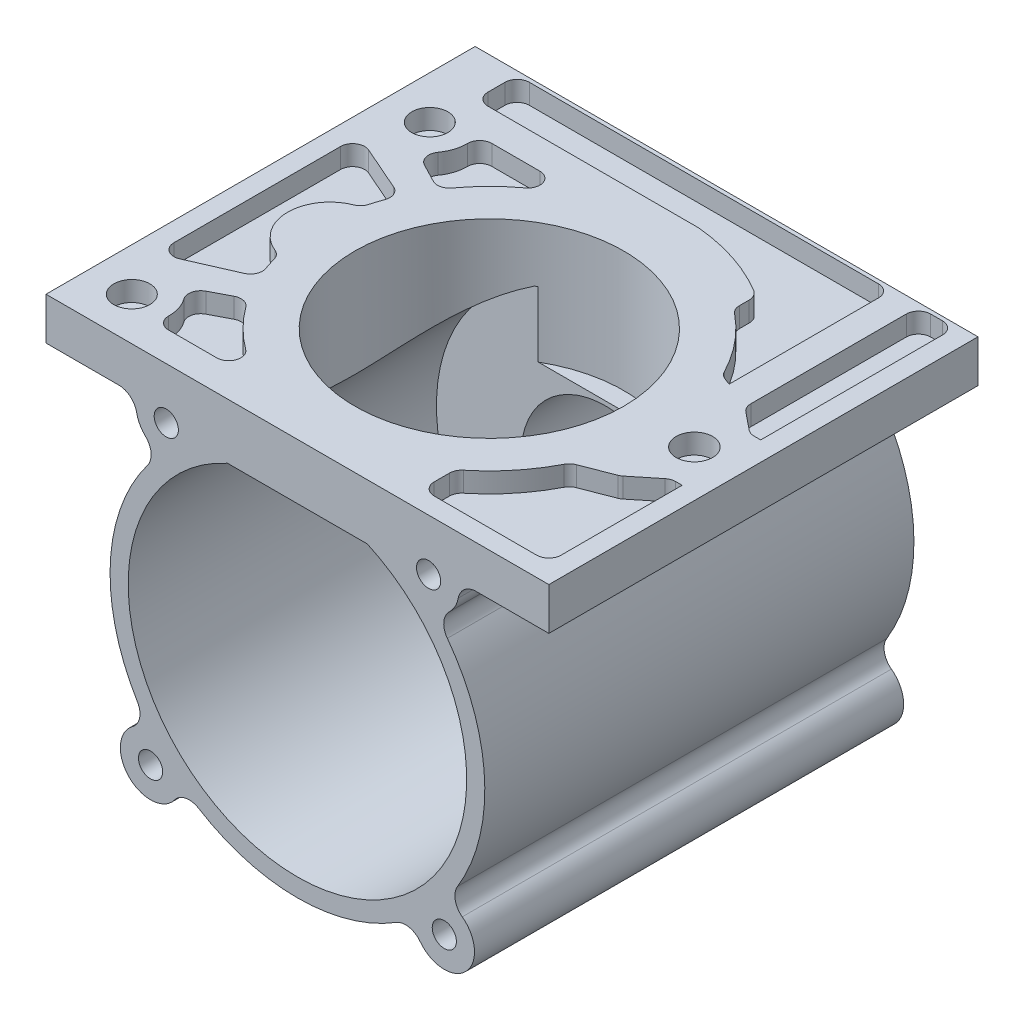
SolidWorks part; units mm, degrees
ref_plane "Front Plane" through (0, 0, 0) normal (0, 0, 1) x (1, 0, 0)
ref_plane "Top Plane" through (0, 0, 0) normal (0, 1, 0) x (1, 0, 0)
ref_plane "Right Plane" through (0, 0, 0) normal (1, 0, 0) x (0, 0, -1)
sketch "Sketch1" plane through (0, 0, 0) normal (0, 0, 1) x (1, 0, 0)
  line L0 (0, -28) -> (0, 25.5) construction
  line L1 (0, 25.5) -> (-11.565, 25.5)
  line L2 (0, 25.5) -> (11.565, 25.5)
  line L3 (0, 25.5) -> (0, 34.7) construction
  line L4 (-41.6, 34.7) -> (41.6, 34.7)
  line L5 (-41.6, 34.7) -> (-41.6, 27.7)
  line L6 (-41.6, 27.7) -> (-29.5581, 27.7)
  line L7 (41.6, 34.7) -> (41.6, 27.7)
  line L8 (41.6, 27.7) -> (29.5581, 27.7)
  line L9 (0, 0) -> (-24.3, -24.1) construction
  line L10 (0, -24.1) -> (-24.3, -24.1) construction
  line L11 (-21.7, 26.2) -> (0, 26.2) construction
  line L12 (-21.7, 26.2) -> (-24.3, -24.1) construction
  line L13 (-21.7, 28.2) -> (-21.7, 34.7) construction
  arc A0 (-11.565, 25.5) -> (11.565, 25.5) centre (0, 0) ccw
  arc A1 (-16.3237, -26.3541) -> (16.3237, -26.3541) centre (0, 0) ccw
  circle A2 centre (-24.3, -24.1) radius 2
  circle A3 centre (24.3, -24.1) radius 2
  circle A4 centre (-21.7, 26.2) radius 2
  circle A5 centre (21.7, 26.2) radius 2
  arc A6 (-26.6113, 25.2625) -> (-25.1401, 22.5715) centre (-21.7, 26.2) ccw
  arc A7 (-27.2697, -20.0774) -> (-20.3021, -27.1028) centre (-24.3, -24.1) ccw
  arc A8 (20.3021, -27.1028) -> (27.2697, -20.0774) centre (24.3, -24.1) ccw
  arc A9 (25.1401, 22.5715) -> (26.6113, 25.2625) centre (21.7, 26.2) ccw
  arc A10 (26.4881, -16.1053) -> (24.8038, 18.5949) centre (0, 0) ccw
  arc A11 (-24.8038, 18.5949) -> (-26.4881, -16.1053) centre (0, 0) ccw
  arc A12 (27.2697, -20.0774) -> (26.4881, -16.1053) centre (29.0515, -17.6639) cw
  arc A13 (20.3021, -27.1028) -> (16.3237, -26.3541) centre (17.9034, -28.9045) ccw
  arc A14 (-27.2697, -20.0774) -> (-26.4881, -16.1053) centre (-29.0515, -17.6639) ccw
  arc A15 (-20.3021, -27.1028) -> (-16.3237, -26.3541) centre (-17.9034, -28.9045) cw
  arc A16 (25.1401, 22.5715) -> (24.8038, 18.5949) centre (27.2042, 20.3945) ccw
  arc A17 (-26.6113, 25.2625) -> (-29.5581, 27.7) centre (-29.5581, 24.7) ccw
  arc A18 (-25.1401, 22.5715) -> (-24.8038, 18.5949) centre (-27.2042, 20.3945) cw
  arc A19 (26.6113, 25.2625) -> (29.5581, 27.7) centre (29.5581, 24.7) cw
  point P12 (0, 34.7)
  point P34 (24.416, -19.1013)
  point P43 (22.5494, 21.2727)
  point P48 (-22.5494, 21.2727)
  dimension "D1" = 56
  dimension "D2" = 3
  dimension "D4" = 24.3
  dimension "D5" = 21.7
  dimension "D6" = 4
  dimension "D12" = 3
  dimension "D13" = 3
  dimension "D14" = 3
  dimension "D3" = 83.2
  dimension "D7" = 50.3
  dimension "D8" = 6.5
  dimension "D9" = 7
  dimension "D10" = 9.2
  dimension "D11" = 53.5
extrude "Boss-Extrude1" add sketch "Sketch1" against normal blind 71
sketch "Sketch3" plane through (0, 0, -71) normal (0, 0, -1) x (-1, 0, 0)
  line L0 (-11.565, 25.5) -> (11.565, 25.5) construction
  line L1 (-11.565, 25.5) -> (11.565, 25.5)
  arc A0 (-11.565, 25.5) -> (11.565, 25.5) centre (0, 0) ccw construction
  arc A1 (-11.565, 25.5) -> (11.565, 25.5) centre (0, 0) ccw
extrude "Boss-Extrude2" add sketch "Sketch3" against normal blind 20
sketch "Sketch4" plane through (0, 34.7, 0) normal (0, 1, 0) x (1, 0, 0)
  line L0 (0, 0) -> (0, 9.5) construction
  circle A0 centre (0, 31.75) radius 22.25
  dimension "D1" = 44.5
  dimension "D2" = 9.5
extrude "Cut-Extrude1" cut sketch "Sketch4" against normal blind 20
sketch "Sketch5" plane through (0, 34.7, 0) normal (0, 1, 0) x (1, 0, 0)
  line L0 (-41.6, 0) -> (17.4, 0)
  line L1 (41.6, 0) -> (-41.6, 0) construction
  line L2 (17.4, 5.2229) -> (17.4, 7.7523)
  line L3 (28.85, 31.75) -> (41.6, 31.75) construction
  line L4 (41.6, 71) -> (41.6, 0) construction
  line L5 (41.6, 25.25) -> (41.6, 38.25)
  line L6 (38.4, 38.25) -> (37.315, 38.25)
  line L7 (36.0438, 38.6993) -> (33.1517, 41.0356)
  line L8 (27.8, 43.6185) -> (26.6923, 44.0468)
  line L9 (36.95, 31.75) -> (41.6, 31.75) construction
  line L10 (38.4, 25.25) -> (37.315, 25.25)
  line L11 (36.0438, 24.8007) -> (32.1789, 21.6786)
  line L12 (31.6373, 21.3654) -> (26.6923, 19.4532)
  line L13 (17.4, 8.7378) -> (17.4, 54.7622) construction
  line L14 (-41.6, 71) -> (-41.6, 0) construction
  line L15 (-28.85, 31.75) -> (-41.6, 31.75) construction
  line L16 (-31.9771, 63.5) -> (2.8161, 63.5)
  line L17 (17.4, 57.3365) -> (17.4, 55.7477)
  line L18 (-41.6, 0) -> (-41.6, 13.5)
  line L19 (-41.6, 63.5) -> (-41.6, 50)
  line L20 (-38.4, 48.5962) -> (0, 31.75) construction
  line L21 (0, 31.75) -> (-38.4, 14.9038) construction
  line L22 (-35.5965, 47.3663) -> (-28.1915, 44.1177)
  line L23 (-35.5965, 16.1337) -> (-28.1915, 19.3823)
  line L24 (-41.6, 50) -> (-41.6, 13.5)
  line L25 (-38.4, 45.5348) -> (-38.4, 17.9652)
  line L27 (-34, 65.5229) -> (-34, 68.3305)
  line L28 (41.6, 71) -> (-41.6, 71) construction
  line L29 (-34, 71) -> (-41.6, 71)
  line L30 (-41.6, 71) -> (-41.6, 63.5)
  line L31 (17.4, 0) -> (41.6, 0)
  line L32 (41.6, 0) -> (41.6, 25.25)
  line L33 (38.4, 25.25) -> (38.4, 5.2229)
  line L34 (36.3771, 3.2) -> (19.4229, 3.2)
  line L35 (-18.3697, 5.0073) -> (-26.3348, 5.0073)
  line L36 (-25.7564, 15.2693) -> (-28.8179, 13.6674)
  line L37 (-18.3697, 58.4927) -> (-26.3348, 58.4927)
  line L38 (-25.7564, 48.2307) -> (-28.8179, 49.8326)
  line L39 (38.4, 38.25) -> (38.4, 68.3305)
  line L40 (38.4, 71) -> (41.6, 71)
  line L41 (41.6, 71) -> (41.6, 38.25)
  line L42 (38.4, 71) -> (32.4, 71)
  line L43 (32.4, 68.3305) -> (32.4, 42.6092)
  line L44 (32.4, 71) -> (27.8, 71)
  line L45 (27.8, 68.3305) -> (27.8, 43.6185)
  line L46 (-34, 71) -> (27.8, 71)
  line L47 (-31.9771, 70.3534) -> (25.7771, 70.3534)
  line L48 (34.4229, 70.3534) -> (36.3771, 70.3534)
  circle A0 centre (0, 31.75) radius 22.25 construction
  arc A1 (-27.7703, 23.9311) -> (-27.1153, 21.8969) centre (0, 31.75) ccw
  circle A2 centre (33.9279, 31.75) radius 3.0221
  circle A3 centre (-34.5, 7.1) radius 2.9845
  circle A4 centre (-34.5, 56.4) radius 2.9845
  arc A5 (2.8161, 63.5) -> (16.4191, 59.0704) centre (0, 31.75) cw
  arc A6 (-28.9552, 38.253) -> (-28.9552, 25.247) centre (-26.3646, 31.75) ccw
  arc A7 (-27.1153, 41.6031) -> (-27.7703, 39.5689) centre (0, 31.75) ccw
  arc A8 (18.1503, 9.3248) -> (25.6251, 18.4958) centre (0, 31.75) ccw
  arc A9 (25.6251, 45.0042) -> (18.1503, 54.1752) centre (0, 31.75) ccw
  arc A10 (-23.2177, 14.6819) -> (-17.1775, 8.6131) centre (0, 31.75) ccw
  arc A11 (-28.3347, 7.03) -> (-29.5094, 10.7208) centre (-34.5, 7.1) ccw
  arc A12 (-23.2177, 14.6819) -> (-25.7564, 15.2693) centre (-24.8292, 13.4973) ccw
  arc A13 (-17.1775, 8.6131) -> (-18.3697, 5.0073) centre (-18.3697, 7.0073) cw
  arc A14 (-26.3348, 5.0073) -> (-28.3347, 7.03) centre (-26.3348, 7.0073) cw
  arc A15 (-29.5094, 10.7208) -> (-28.8179, 13.6674) centre (-27.8906, 11.8953) cw
  arc A16 (-23.2177, 48.8181) -> (-17.1775, 54.8869) centre (0, 31.75) cw
  arc A17 (-17.1775, 54.8869) -> (-18.3697, 58.4927) centre (-18.3697, 56.4927) ccw
  arc A18 (-26.3348, 58.4927) -> (-28.3347, 56.47) centre (-26.3348, 56.4927) ccw
  arc A19 (-28.3347, 56.47) -> (-29.5094, 52.7792) centre (-34.5, 56.4) cw
  arc A20 (-23.2177, 48.8181) -> (-25.7564, 48.2307) centre (-24.8292, 50.0027) cw
  arc A21 (-29.5094, 52.7792) -> (-28.8179, 49.8326) centre (-27.8906, 51.6047) ccw
  arc A22 (-38.4, 17.9652) -> (-35.5965, 16.1337) centre (-36.4, 17.9652) ccw
  arc A23 (-28.1915, 19.3823) -> (-27.1153, 21.8969) centre (-28.995, 21.2138) ccw
  arc A24 (-28.9552, 25.247) -> (-27.7703, 23.9311) centre (-29.6954, 23.389) cw
  arc A25 (-28.9552, 38.253) -> (-27.7703, 39.5689) centre (-29.6954, 40.111) ccw
  arc A26 (-28.1915, 44.1177) -> (-27.1153, 41.6031) centre (-28.995, 42.2862) cw
  arc A27 (-38.4, 45.5348) -> (-35.5965, 47.3663) centre (-36.4, 45.5348) cw
  arc A28 (-31.9771, 70.3534) -> (-34, 68.3305) centre (-31.9771, 68.3305) ccw
  arc A29 (27.8, 68.3305) -> (25.7771, 70.3534) centre (25.7771, 68.3305) ccw
  arc A30 (34.4229, 70.3534) -> (32.4, 68.3305) centre (34.4229, 68.3305) ccw
  arc A31 (38.4, 68.3305) -> (36.3771, 70.3534) centre (36.3771, 68.3305) ccw
  arc A32 (32.1789, 21.6786) -> (31.6373, 21.3654) centre (30.9077, 23.2522) cw
  arc A33 (37.315, 25.25) -> (36.0438, 24.8007) centre (37.315, 23.2271) ccw
  arc A34 (38.4, 5.2229) -> (36.3771, 3.2) centre (36.3771, 5.2229) cw
  arc A35 (19.4229, 3.2) -> (17.4, 5.2229) centre (19.4229, 5.2229) cw
  arc A36 (-31.9771, 63.5) -> (-34, 65.5229) centre (-31.9771, 65.5229) cw
  arc A37 (17.4, 7.7523) -> (18.1503, 9.3248) centre (19.4229, 7.7523) cw
  arc A38 (26.6923, 19.4532) -> (25.6251, 18.4958) centre (27.422, 17.5664) ccw
  arc A39 (37.315, 38.25) -> (36.0438, 38.6993) centre (37.315, 40.2729) cw
  arc A40 (32.4, 42.6092) -> (33.1517, 41.0356) centre (34.4229, 42.6092) ccw
  arc A41 (26.6923, 44.0468) -> (25.6251, 45.0042) centre (27.422, 45.9336) cw
  arc A42 (18.1503, 54.1752) -> (17.4, 55.7477) centre (19.4229, 55.7477) cw
  arc A43 (16.4191, 59.0704) -> (17.4, 57.3365) centre (15.3771, 57.3365) cw
  point P17 (41.6, 31.75)
  point P97 (-26.4195, 20.1597)
  point P104 (-26.4195, 43.3403)
  point P120 (36.6, 25.25)
  point P132 (25.9634, 19.1713)
  point P135 (36.6, 38.25)
  point P140 (25.9634, 44.3287)
  dimension "D1" = 6.6
  dimension "D3" = 44.5
  dimension "D8" = 4.65
  dimension "D9" = 7.1
  dimension "D11" = 13.5
  dimension "D13" = 14
  dimension "D17" = 2
  dimension "D6" = 2
  dimension "D7" = 2.0229
  dimension "D2" = 59
  dimension "D4" = 13
  dimension "D5" = 5
  dimension "D10" = 7.1
  dimension "D12" = 13.5
  dimension "D14" = 3.2
  dimension "D15" = 3.2
  dimension "D16" = 3.2
  dimension "D18" = 3.2
  dimension "D19" = 6
  dimension "D20" = 4.6
extrude "Cut-Extrude2" cut sketch "Sketch5" against normal blind 3.3 contours L8 A41 A9 A42 L17 A43 A5 L16 A36 L27 A28 L47 A29 L45 | L6 A39 L7 A40 L43 A30 L48 A31 L39 | A16 A17 L37 A18 A19 A21 L38 A20 | A4 | A1 A24 A6 A25 A7 A26 L22 A27 L25 A22 L23 A23 | A3 | A15 A11 A14 L35 A13 A10 A12 L36 | A8 A38 L12 A32 L11 A33 L10 L33 A34 L34 A35 L2 A37 | A2
sketch "Sketch6" plane through (0, 0, -71) normal (0, 0, -1) x (-1, 0, 0)
  circle A0 centre (-21.7, 26.2) radius 2
  circle A1 centre (21.7, 26.2) radius 2
  circle A2 centre (24.3, -24.1) radius 2
  circle A3 centre (-24.3, -24.1) radius 2
extrude "Boss-Extrude3" add sketch "Sketch6" against normal blind 53.3
sketch "Sketch7" plane through (0, 34.7, 0) normal (0, 1, 0) x (1, 0, 0)
  circle A0 centre (0, 31.75) radius 22.25
extrude "Cut-Extrude4" cut sketch "Sketch7" against normal up to surface (20 mm away) up to face at (0, 14.7, -52.5)
sketch "Sketch8" plane through (0, 0, -51) normal (0, 0, 1) x (1, 0, 0)
  circle A0 centre (0, 0) radius 14
extrude "Cut-Extrude5" cut sketch "Sketch8" against normal blind 29
